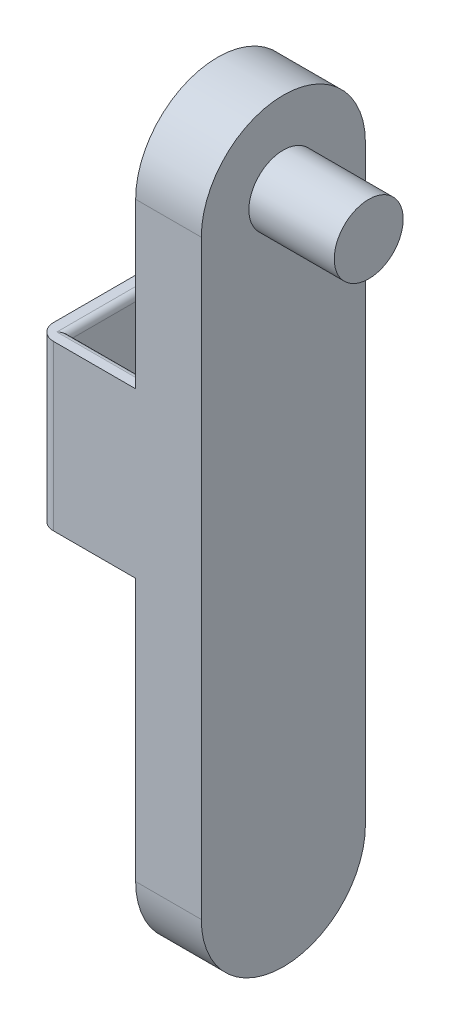
SolidWorks part; units mm, degrees
ref_plane "Front Plane" through (0, 0, 0) normal (0, 0, 1) x (1, 0, 0)
ref_plane "Top Plane" through (0, 0, 0) normal (0, 1, 0) x (1, 0, 0)
ref_plane "Right Plane" through (0, 0, 0) normal (1, 0, 0) x (0, 0, -1)
sketch "Sketch1" plane through (0, 0, 0) normal (1, 0, 0) x (0, 0, -1)
  line L0 (-17.2349, 15.5155) -> (-17.2349, -2.4845)
  line L1 (-12.2349, 15.5155) -> (-12.2349, -2.4845)
  arc A0 (-17.2349, 15.5155) -> (-12.2349, 15.5155) centre (-14.7349, 15.5155) cw
  arc A1 (-12.2349, -2.4845) -> (-17.2349, -2.4845) centre (-14.7349, -2.4845) cw
  dimension "D1" = 18
  dimension "D2" = 5
extrude "Boss-Extrude1" add sketch "Sketch1" along normal blind 2
sketch "Sketch2" plane through (2, 0, 0) normal (1, 0, 0) x (0, 0, -1)
  circle A0 centre (-14.7349, 15.5155) radius 1.05
  dimension "D1" = 2.1
extrude "Boss-Extrude2" add sketch "Sketch2" along normal blind 2.6
sketch "Sketch3" plane through (0, 0, 12.2349) normal (0, 0, -1) x (-1, 0, 0)
  line L0 (0, -2.4845) -> (0, 15.5155) construction
  line L1 (0, 10.5155) -> (3, 10.5155)
  line L2 (0, 10.5155) -> (0, 5.5155)
  line L3 (0, 5.5155) -> (3, 5.5155)
  line L4 (3, 10.5155) -> (3, 5.5155)
  line L5 (-2, 15.5155) -> (0, 15.5155) construction
  dimension "D1" = 3
  dimension "D2" = 5
  dimension "D3" = 5
extrude "Boss-Extrude3" add sketch "Sketch3" against normal up to surface (5 mm away) up to face at (1, 6.5155, 17.2349)
sketch "Sketch4" plane through (0, 10.5155, 0) normal (0, 1, 0) x (1, 0, 0)
  line L0 (0, -17.2349) -> (-3, -17.2349) construction
  line L1 (-0.5, -16.7349) -> (-2.5, -16.7349)
  line L2 (-0.5, -16.7349) -> (-0.5, -12.7349)
  line L3 (-0.5, -12.7349) -> (-2.5, -12.7349)
  line L4 (-2.5, -16.7349) -> (-2.5, -12.7349)
  line L5 (-3, -12.2349) -> (0, -12.2349) construction
  line L6 (-3, -17.2349) -> (-3, -12.2349) construction
  line L7 (0, -17.2349) -> (0, -12.2349) construction
  dimension "D1" = 0.5
  dimension "D2" = 0.5
  dimension "D3" = 0.5
  dimension "D4" = 0.5
extrude "Cut-Extrude1" cut sketch "Sketch4" against normal through all
fillet "Fillet1" radius 0.5 2 edges at (-3, 8.0155, 17.2349) (-3, 8.0155, 12.2349)
fillet "Fillet2" radius 0.2 8 edges at (-1.5, 5.5155, 12.7349) (-2.5, 5.5155, 14.7349) (-1.5, 5.5155, 16.7349) (-0.5, 5.5155, 14.7349) (-2.5, 10.5155, 14.7349) (-1.5, 10.5155, 16.7349) (-1.5, 10.5155, 12.7349) (-0.5, 10.5155, 14.7349)
